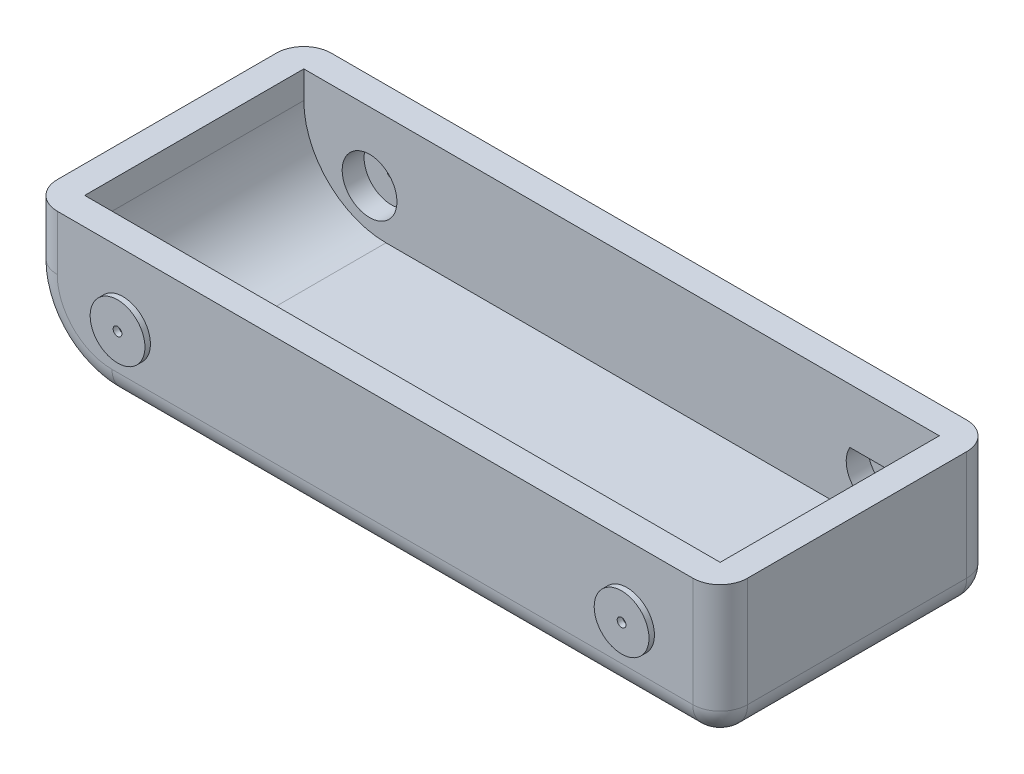
SolidWorks part; units mm, degrees
ref_plane "Front Plane" through (0, 0, 0) normal (0, 0, 1) x (1, 0, 0)
ref_plane "Top Plane" through (0, 0, 0) normal (0, 1, 0) x (1, 0, 0)
ref_plane "Right Plane" through (0, 0, 0) normal (1, 0, 0) x (0, 0, -1)
sketch "Sketch1" plane through (0, 0, 0) normal (0, 1, 0) x (1, 0, 0)
  line L1 (0, 0) -> (126, 0)
  line L2 (0, 0) -> (0, 50)
  line L3 (0, 50) -> (126, 50)
  line L4 (126, 0) -> (126, 50)
  dimension "D1" = 50
  dimension "D2" = 126
extrude "Boss-Extrude1" add sketch "Sketch1" along normal blind 25
sketch "Sketch3" plane through (0, 25, 0) normal (0, 1, 0) x (1, 0, 0)
  line L0 (0, 50) -> (0, 0) construction
  line L1 (5, 45) -> (121, 45)
  line L2 (5, 45) -> (5, 5)
  line L3 (5, 5) -> (121, 5)
  line L4 (121, 45) -> (121, 5)
  line L5 (126, 0) -> (126, 50) construction
  line L6 (126, 50) -> (0, 50) construction
  line L7 (0, 0) -> (126, 0) construction
  dimension "D1" = 5
  dimension "D2" = 5
  dimension "D3" = 5
  dimension "D4" = 5
extrude "Cut-Extrude1" cut sketch "Sketch3" against normal blind 20
fillet "Fillet1" radius 15 1 edges at (0, 0, -25)
fillet "Fillet2" radius 15 1 edges at (5, 5, -25)
sketch "Sketch4" plane through (0, 0, -50) normal (0, 0, -1) x (-1, 0, 0)
  line L0 (0, 15) -> (-126, 15) construction
  line L1 (-126, 25) -> (-126, 0) construction
  line L2 (0, 15) -> (-15, 15)
  line L3 (-126, 25) -> (0, 25)
  line L4 (-126, 15) -> (-75, 15)
  line L5 (-63, 25) -> (-63, 0) construction
  line L6 (-126, 0) -> (-15, 0) construction
  circle A0 centre (-109, 12.5) radius 5
  circle A1 centre (-17, 12.5) radius 5
  dimension "D1" = 2.5
  dimension "D2" = 17
  dimension "D3" = 10
extrude "Cut-Extrude2" cut sketch "Sketch4" along normal blind 4 from offset 5 offset against normal yes
sketch "Sketch9" plane through (0, 0, -50) normal (0, 0, -1) x (-1, 0, 0)
  circle A0 centre (-109, 12.5) radius 5
  circle A2 centre (-17, 12.5) radius 5
extrude "Boss-Extrude5" add sketch "Sketch9" along normal blind 1 contours A0 | A2
sketch "Sketch11" plane through (0, 0, -51) normal (0, 0, -1) x (-1, 0, 0)
  circle A0 centre (-17, 12.5) radius 0.8
  circle A1 centre (-109, 12.5) radius 0.8
extrude "Cut-Extrude5" cut sketch "Sketch11" against normal blind 5
fillet "Fillet3" radius 5 2 edges at (126, 12.5, -50) (126, 12.5, 0)
fillet "Fillet4" radius 5 9 edges at (0, 20, 0) (4.3934, 4.3934, 0) (68, 0, 0) (124.5355, 0, -1.4645) (0, 20, -50) (4.3934, 4.3934, -50) (68, 0, -50) (124.5355, 0, -48.5355) (126, 0, -25)
sketch "Sketch12" plane through (0, 0, 0) normal (0, 0, 1) x (1, 0, 0)
  circle A0 centre (17, 12.5) radius 5
  circle A1 centre (109, 12.5) radius 5
extrude "Boss-Extrude6" add sketch "Sketch12" along normal blind 1
sketch "Sketch13" plane through (0, 0, -5) normal (0, 0, -1) x (-1, 0, 0)
  circle A0 centre (-109, 12.5) radius 5
  circle A2 centre (-17, 12.5) radius 5
extrude "Cut-Extrude8" cut sketch "Sketch13" against normal up to surface (5 mm away) up to face at (104, 12.5, 0)
sketch "Sketch14" plane through (0, 0, 0) normal (0, 0, 1) x (1, 0, 0)
  circle A0 centre (17, 12.5) radius 0.8
  circle A1 centre (109, 12.5) radius 0.8
extrude "Cut-Extrude9" cut sketch "Sketch14" along normal blind 5
